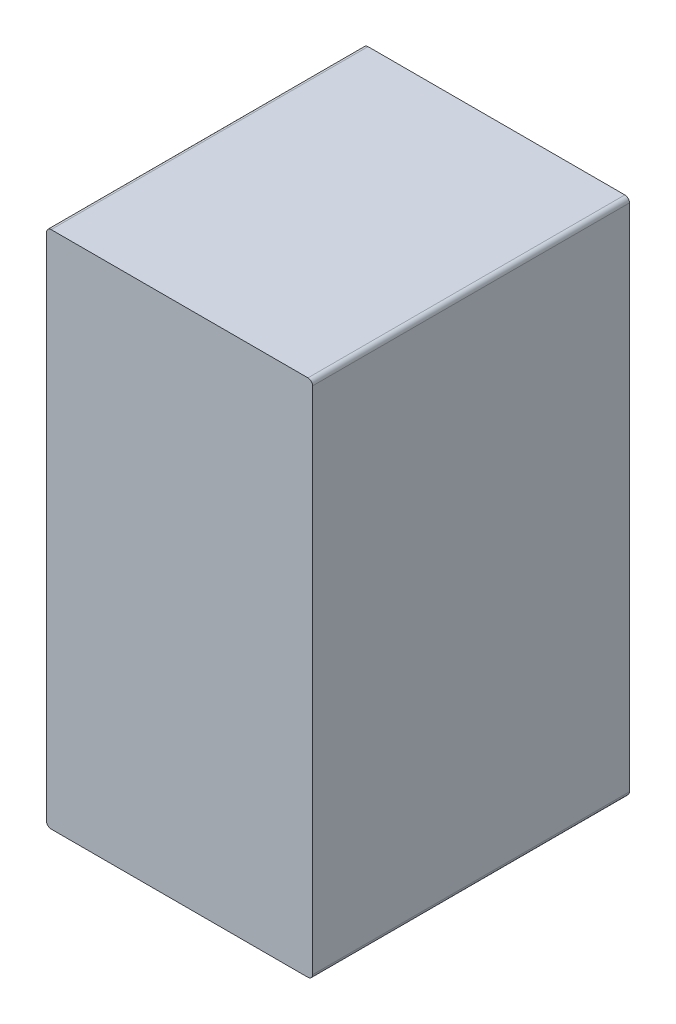
SolidWorks part; units mm, degrees
ref_plane "Front Plane" through (0, 0, 0) normal (0, 0, 1) x (1, 0, 0)
ref_plane "Top Plane" through (0, 0, 0) normal (0, 1, 0) x (1, 0, 0)
ref_plane "Right Plane" through (0, 0, 0) normal (1, 0, 0) x (0, 0, -1)
sketch "Sketch1" plane through (0, 0, 0) normal (0, 0, 1) x (1, 0, 0)
  line L0 (0, 0) -> (0, 145.7232) construction
  line L1 (-69.5, -139) -> (69.5, -139)
  line L2 (-70.5, -138) -> (-70.5, 138)
  line L3 (-69.5, 139) -> (69.5, 139)
  line L4 (70.5, -138) -> (70.5, 138)
  line L5 (-70.5, -139) -> (70.5, 139) construction
  line L6 (-70.5, 139) -> (70.5, -139) construction
  line L7 (0, 145.7232) -> (-68, 38.9846)
  line L8 (-65.5, 9.4079) -> (-1.6868, 109.5746) construction
  line L9 (-68.0302, 11.0198) -> (-4.217, 111.1865) construction
  line L10 (-65.5, 9.4079) -> (-68.0302, 11.0198) construction
  line L11 (-65.5, 9.4079) -> (-65.5, 8.4079) construction
  line L12 (-65.5, 8.4079) -> (-70.5, 8.4079) construction
  line L13 (-70.5, 8.4079) -> (-70.5, 37.3253) construction
  line L14 (-67.217, 40.2137) -> (-16.8678, 119.246) construction
  line L15 (-68, 14.5577) -> (-68, 37.5272) construction
  line L16 (-18.5546, 120.3206) -> (-69.717, 40.0118) construction
  line L17 (65.5, 9.4079) -> (65.5, 8.4079) construction
  line L18 (65.5, 9.4079) -> (68.0302, 11.0198) construction
  line L19 (65.5, 8.4079) -> (70.5, 8.4079) construction
  line L20 (70.5, 8.4079) -> (70.5, 37.3253) construction
  line L21 (68, 14.5577) -> (68, 37.5272) construction
  line L22 (65.5, 9.4079) -> (1.6868, 109.5746) construction
  line L23 (68.0302, 11.0198) -> (4.217, 111.1865) construction
  line L24 (67.217, 40.2137) -> (16.8678, 119.246) construction
  line L25 (18.5546, 120.3206) -> (69.717, 40.0118) construction
  line L26 (-68.0302, 11.0198) -> (-66.4183, 13.55) construction
  line L27 (-66.4183, 13.55) -> (-68, 14.5577) construction
  line L28 (66.4183, 13.55) -> (68, 14.5577) construction
  line L29 (-65.5, 8.4079) -> (-65.5, 3.4079) construction
  line L30 (-65.5, 3.4079) -> (-15.1236, -135) construction
  line L31 (-15.1236, -135) -> (15.1236, -135) construction
  line L32 (25.5253, -74.8874) -> (65.5, 3.4079) construction
  line L33 (17.9245, -139) -> (-17.9245, -139) construction
  line L34 (-17.9245, -139) -> (-70.5, 5.4501) construction
  line L35 (-70.5, 5.4501) -> (-70.5, 8.4079) construction
  line L36 (-70.5, 8.4079) -> (-70.5, 5.4501) construction
  line L37 (65.5, 3.4079) -> (15.1236, -135) construction
  line L38 (17.9245, -139) -> (70.5, 5.4501) construction
  line L39 (65.5, 8.4079) -> (70.5, 8.4079) construction
  line L40 (65.5, 8.4079) -> (65.5, 3.4079) construction
  line L41 (70.5, 5.4501) -> (70.5, 8.4079) construction
  line L42 (-25.5253, -74.8874) -> (-65.5, 3.4079) construction
  line L44 (69.5, 140.5) -> (-69.5, 140.5)
  line L45 (72, 138) -> (72, -138)
  line L46 (69.5, -140.5) -> (-69.5, -140.5)
  line L47 (-72, 138) -> (-72, -138)
  line L48 (72, 140.5) -> (-72, -140.5) construction
  line L49 (72, -140.5) -> (-72, 140.5) construction
  arc A0 (-1.6868, 109.5746) -> (1.6868, 109.5746) centre (0, 108.5) cw construction
  arc A1 (-4.217, 111.1865) -> (4.217, 111.1865) centre (0, 108.5) cw construction
  arc A2 (-16.8678, 119.246) -> (16.8678, 119.246) centre (0, 108.5) cw construction
  arc A3 (-69.717, 40.0118) -> (-70.5, 37.3253) centre (-65.5, 37.3253) ccw construction
  arc A4 (-67.217, 40.2137) -> (-68, 37.5272) centre (-63, 37.5272) ccw construction
  arc A5 (-18.5546, 120.3206) -> (18.5546, 120.3206) centre (0, 108.5) cw construction
  arc A6 (67.217, 40.2137) -> (68, 37.5272) centre (63, 37.5272) cw construction
  arc A7 (69.717, 40.0118) -> (70.5, 37.3253) centre (65.5, 37.3253) cw construction
  arc A9 (-25.5253, -74.8874) -> (25.5253, -74.8874) centre (0, -61.8551) ccw construction
  circle A10 centre (-1.6868, -115) radius 11 construction
  arc A11 (-70.5, 138) -> (-69.5, 139) centre (-69.5, 138) cw
  arc A12 (69.5, 139) -> (70.5, 138) centre (69.5, 138) cw
  arc A13 (69.5, -139) -> (70.5, -138) centre (69.5, -138) ccw
  arc A14 (-70.5, -138) -> (-69.5, -139) centre (-69.5, -138) ccw
  arc A15 (69.5, -140.5) -> (72, -138) centre (69.5, -138) ccw
  arc A16 (-72, -138) -> (-69.5, -140.5) centre (-69.5, -138) ccw
  arc A17 (-72, 138) -> (-69.5, 140.5) centre (-69.5, 138) cw
  arc A18 (69.5, 140.5) -> (72, 138) centre (69.5, 138) cw
  point P0 (0, 0)
  point P24 (-70.5, 38.7827)
  dimension "D5" = 2
  dimension "D10" = 5
  dimension "D21" = 22
  dimension "D24" = 1
  dimension "D25" = 2.5
  dimension "D1" = 141
  dimension "D2" = 278
  dimension "D3" = 32.5
  dimension "D4" = 3
  dimension "D6" = 15
  dimension "D7" = 1
  dimension "D8" = 5
  dimension "D9" = 2
  dimension "D11" = 30.5
  dimension "D12" = 100.1667
  dimension "D13" = 148.4079
  dimension "D14" = 3
  dimension "D15" = 2.5
  dimension "D16" = 5
  dimension "D17" = 4
  dimension "D18" = 4
  dimension "D19" = 70
  dimension "D20" = 20
  dimension "D22" = 1.5
  dimension "D23" = 1.5
extrude "Boss-Extrude1" add sketch "Sketch1" along normal blind 170
sketch "Sketch2" plane through (0, 0, 170) normal (0, 0, 1) x (1, 0, 0)
  line L1 (-69.5, -140.5) -> (69.5, -140.5)
  line L2 (-72, -138) -> (-72, 138)
  line L3 (-69.5, 140.5) -> (69.5, 140.5)
  line L4 (72, -138) -> (72, 138)
  line L5 (-72, -140.5) -> (72, 140.5) construction
  line L6 (-72, 140.5) -> (72, -140.5) construction
  arc A0 (69.5, -140.5) -> (72, -138) centre (69.5, -138) ccw
  arc A1 (-69.5, -140.5) -> (-72, -138) centre (-69.5, -138) cw
  arc A2 (72, 138) -> (69.5, 140.5) centre (69.5, 138) ccw
  arc A3 (-69.5, 140.5) -> (-72, 138) centre (-69.5, 138) ccw
  point P0 (0, 0)
  dimension "D1" = 2.5
extrude "Boss-Extrude2" add sketch "Sketch2" along normal blind 1.5
